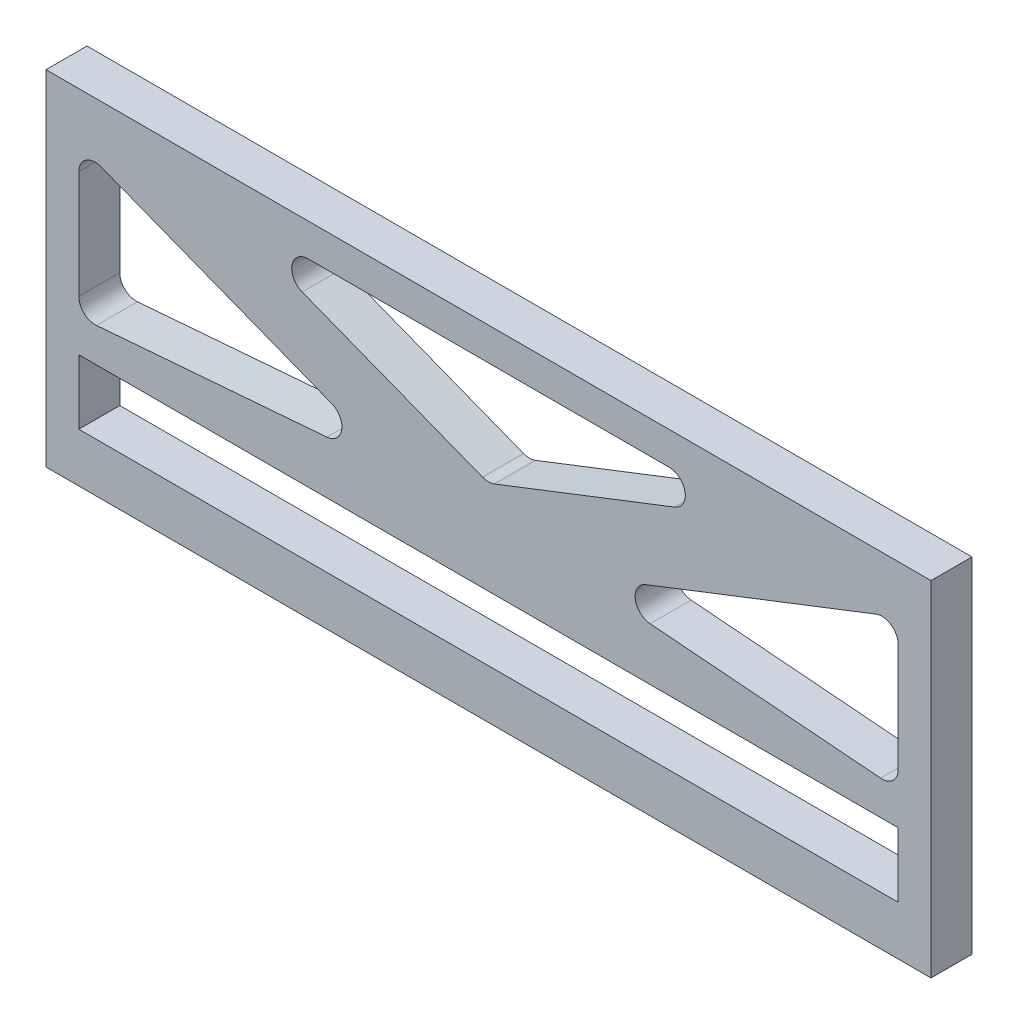
SolidWorks part; units mm, degrees
ref_plane "Front Plane" through (0, 0, 0) normal (0, 0, 1) x (1, 0, 0)
ref_plane "Top Plane" through (0, 0, 0) normal (0, 1, 0) x (1, 0, 0)
ref_plane "Right Plane" through (0, 0, 0) normal (1, 0, 0) x (0, 0, -1)
sketch "Sketch1" plane through (0, 0, 0) normal (0, 0, 1) x (1, 0, 0)
  line L0 (-20.7506, 10.795) -> (0, 2.7253)
  line L1 (-34.29, -13.335) -> (34.29, -13.335)
  line L2 (-34.29, -13.335) -> (-34.29, 13.335)
  line L3 (-34.29, 13.335) -> (34.29, 13.335)
  line L4 (34.29, -13.335) -> (34.29, 13.335)
  line L5 (-34.29, -13.335) -> (34.29, 13.335) construction
  line L6 (-34.29, 13.335) -> (34.29, -13.335) construction
  line L7 (-31.75, -9.525) -> (31.75, -9.525)
  line L8 (-31.75, -9.525) -> (-31.75, -4.525)
  line L9 (-31.75, -4.525) -> (31.75, -4.525)
  line L10 (31.75, -9.525) -> (31.75, -4.525)
  line L11 (-31.75, -9.525) -> (31.75, -4.525) construction
  line L12 (-31.75, -4.525) -> (31.75, -9.525) construction
  line L13 (0, 2.7253) -> (20.7506, 10.795)
  line L14 (20.7506, 10.795) -> (-20.7506, 10.795)
  line L15 (0, 0) -> (0, 2.7253) construction
  line L16 (-10.3753, 6.7602) -> (-11.2959, 4.3929) construction
  line L17 (10.3753, 6.7602) -> (11.2959, 4.3929) construction
  line L18 (0, 10.795) -> (0, 13.335) construction
  line L19 (-31.75, 9.6219) -> (-31.75, -1.985)
  line L20 (-31.75, -1.985) -> (-7.0079, 0)
  line L21 (-7.0079, 0) -> (-31.75, 9.6219)
  line L22 (7.0079, 0) -> (-7.0079, 0) construction
  line L23 (-19.379, 4.811) -> (-18.4584, 7.1782) construction
  line L24 (7.0079, 0) -> (31.75, 9.6219)
  line L25 (31.75, 9.6219) -> (31.75, -1.985)
  line L26 (31.75, -1.985) -> (7.0079, 0)
  line L33 (0, -2.747) -> (0, -4.525) construction
  point P0 (0, 0)
  point P6 (0, -7.025)
  point P27 (0, 0)
  point P39 (0, 0)
  dimension "D1" = 3.81
  dimension "D2" = 2.54
  dimension "D3" = 68.58
  dimension "D4" = 26.67
  dimension "D5" = 5
  dimension "D6" = 2.54
  dimension "D7" = 2.54
  dimension "D8" = 2.54
  dimension "D9" = 1.778
extrude "Boss-Extrude1" add sketch "Sketch1" along normal blind 3.175
fillet "Fillet1" radius 1.27 9 edges at (31.75, 9.6219, 1.5875) (31.75, -1.985, 1.5875) (7.0079, 0, 1.5875) (20.7506, 10.795, 1.5875) (-20.7506, 10.795, 1.5875) (0, 2.7253, 1.5875) (-7.0079, 0, 1.5875) (-31.75, 9.6219, 1.5875) (-31.75, -1.985, 1.5875)
